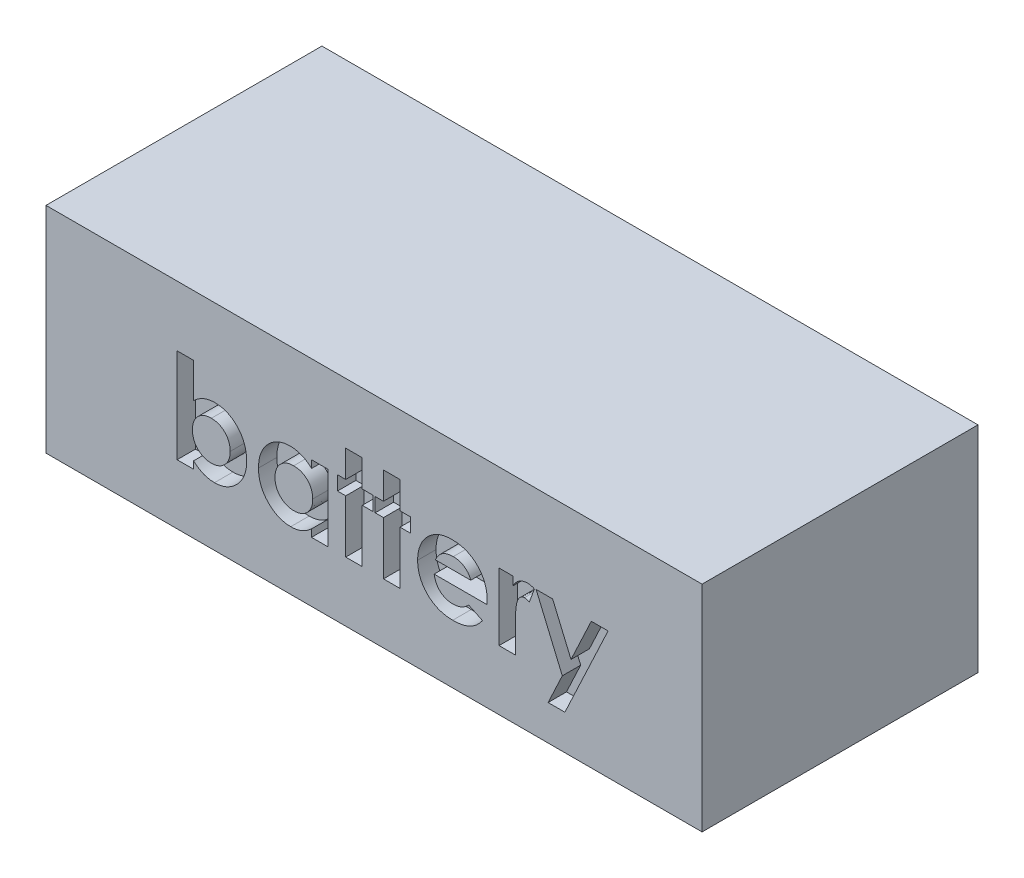
SolidWorks part; units mm, degrees
ref_plane "正面" through (0, 0, 0) normal (0, 0, 1) x (1, 0, 0)
ref_plane "平面" through (0, 0, 0) normal (0, 1, 0) x (1, 0, 0)
ref_plane "右側面" through (0, 0, 0) normal (1, 0, 0) x (0, 0, -1)
sketch "ｽｹｯﾁ1" plane through (0, 0, 0) normal (0, 0, 1) x (1, 0, 0)
  line L1 (0, 0) -> (107, 0)
  line L2 (0, 0) -> (0, 35)
  line L3 (0, 35) -> (107, 35)
  line L4 (107, 0) -> (107, 35)
  dimension "D1" = 107
  dimension "D2" = 35
extrude "ﾎﾞｽ - 押し出し1" add sketch "ｽｹｯﾁ1" along normal blind 45
sketch "ｽｹｯﾁ2" plane through (0, 0, 45) normal (0, 0, 1) x (1, 0, 0)
  text T0 "<b>battery</b>" font "Century Gothic" height 15
extrude "ｶｯﾄ - 押し出し1" cut sketch "ｽｹｯﾁ2" against normal blind 3
